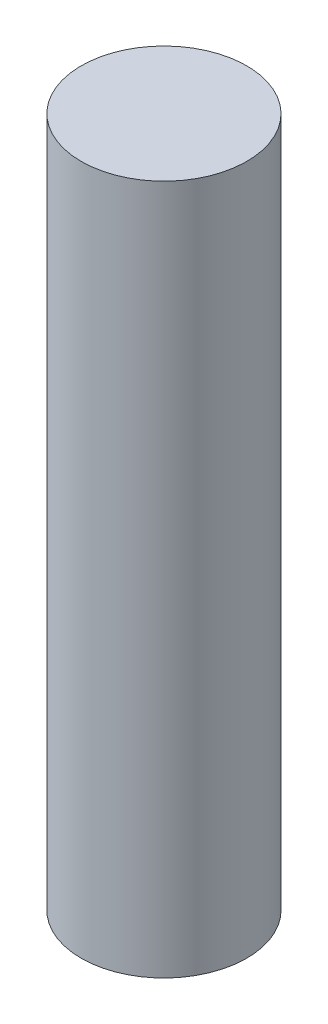
SolidWorks part; units mm, degrees
ref_plane "Front Plane" through (0, 0, 0) normal (0, 0, 1) x (1, 0, 0)
ref_plane "Top Plane" through (0, 0, 0) normal (0, 1, 0) x (1, 0, 0)
ref_plane "Right Plane" through (0, 0, 0) normal (1, 0, 0) x (0, 0, -1)
sketch "Sketch1" plane through (0, 0, 0) normal (0, 1, 0) x (1, 0, 0)
  circle A0 centre (0, 0) radius 18
  dimension "D1" = 36
extrude "Boss-Extrude1" add sketch "Sketch1" along normal blind 150
